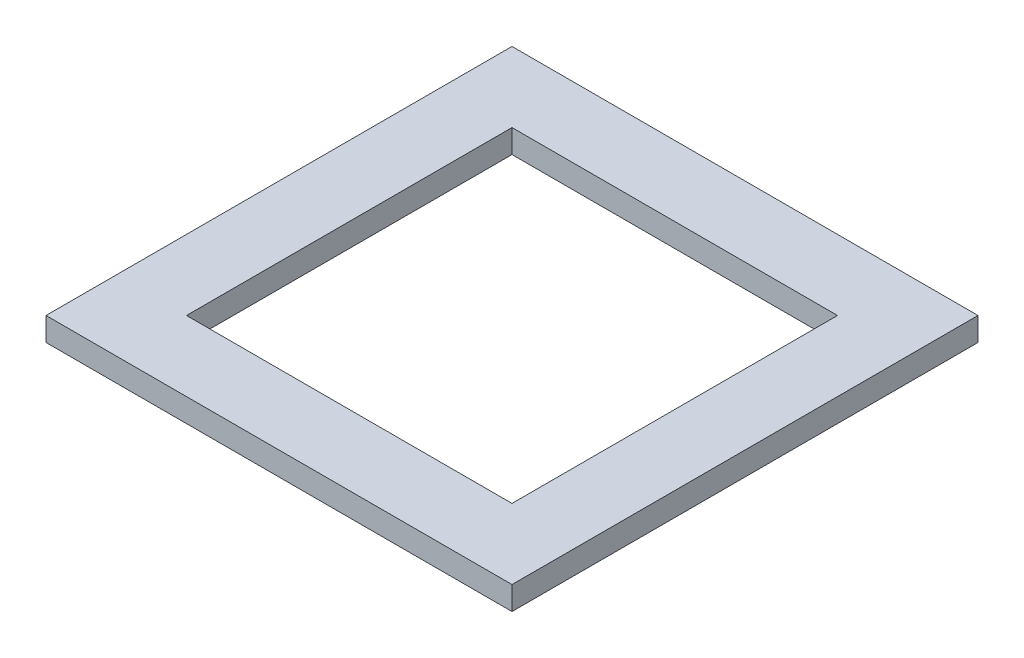
SolidWorks part; units mm, degrees
ref_plane "前视基准面" through (0, 0, 0) normal (0, 0, 1) x (1, 0, 0)
ref_plane "上视基准面" through (0, 0, 0) normal (0, 1, 0) x (1, 0, 0)
ref_plane "右视基准面" through (0, 0, 0) normal (1, 0, 0) x (0, 0, -1)
other "Configuration Table"
sketch "草图4" plane through (0, 0, 0) normal (0, 1, 0) x (1, 0, 0)
  line L1 (-6.95, -6.95) -> (6.95, -6.95)
  line L2 (-6.95, -6.95) -> (-6.95, 6.95)
  line L3 (-6.95, 6.95) -> (6.95, 6.95)
  line L4 (6.95, -6.95) -> (6.95, 6.95)
  line L5 (-6.95, -6.95) -> (6.95, 6.95) construction
  line L6 (-6.95, 6.95) -> (6.95, -6.95) construction
  line L7 (-9.95, -9.95) -> (9.95, -9.95)
  line L8 (-9.95, -9.95) -> (-9.95, 9.95)
  line L9 (-9.95, 9.95) -> (9.95, 9.95)
  line L10 (9.95, -9.95) -> (9.95, 9.95)
  line L11 (-9.95, -9.95) -> (9.95, 9.95) construction
  line L12 (-9.95, 9.95) -> (9.95, -9.95) construction
  point P0 (0, 0)
  point P6 (0, 0)
  dimension "D1" = 13.9
  dimension "D2" = 13.9
  dimension "D3" = 3
  dimension "D4" = 3
extrude "凸台-拉伸1" add sketch "草图4" along normal blind 1 contours L7 L10 L9 L8 L4 L1 L2 L3
